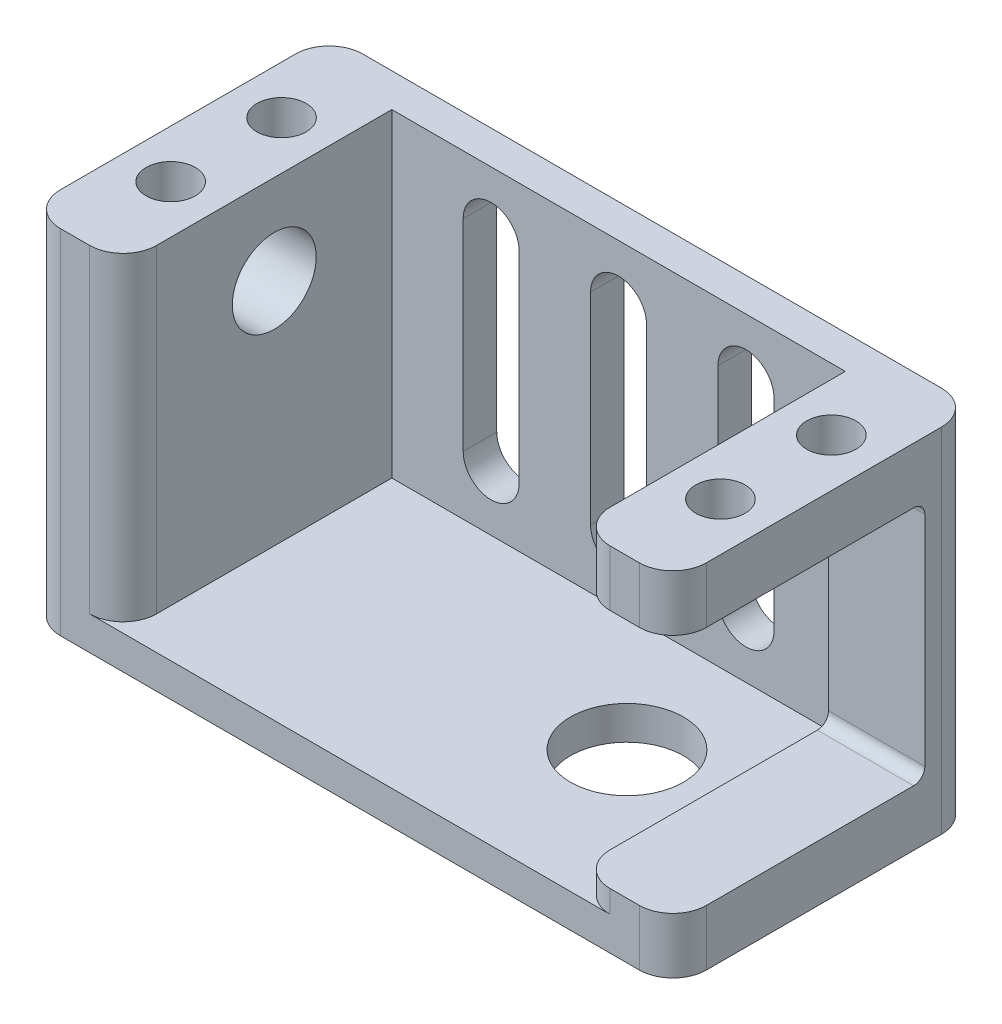
SolidWorks part; units mm, degrees
ref_plane "Front Plane" through (0, 0, 0) normal (0, 0, 1) x (1, 0, 0)
ref_plane "Top Plane" through (0, 0, 0) normal (0, 1, 0) x (1, 0, 0)
ref_plane "Right Plane" through (0, 0, 0) normal (1, 0, 0) x (0, 0, -1)
sketch "Sketch1" plane through (0, 0, 0) normal (0, 1, 0) x (1, 0, 0)
  line L1 (-4.3, -13.5) -> (4.3, -13.5)
  line L2 (-4.3, -13.5) -> (-4.3, 13.5)
  line L3 (-4.3, 13.5) -> (4.3, 13.5)
  line L4 (4.3, -13.5) -> (4.3, 13.5)
  line L5 (-4.3, -13.5) -> (4.3, 13.5) construction
  line L6 (-4.3, 13.5) -> (4.3, -13.5) construction
  point P0 (0, 0)
  dimension "D1" = 8.6
  dimension "D2" = 27
extrude "Boss-Extrude1" add sketch "Sketch1" along normal blind 31.5
sketch "Sketch2" plane through (4.3, 0, 0) normal (1, 0, 0) x (0, 0, -1)
  line L0 (-13.5, 0) -> (13.5, 0)
  line L1 (-13.5, 0) -> (-13.5, 3)
  line L2 (13.5, 0) -> (13.5, 3)
  line L3 (-13.5, 3) -> (13.5, 3)
  line L4 (-13.5, 31.5) -> (-13.5, 0) construction
  line L5 (13.5, 31.5) -> (13.5, 0) construction
  dimension "D1" = 3
extrude "Boss-Extrude2" add sketch "Sketch2" along normal blind 40.5
sketch "Sketch3" plane through (4.3, 0, 0) normal (1, 0, 0) x (0, 0, -1)
  line L0 (10.5, 31.5) -> (10.5, 3)
  line L1 (10.5, 31.5) -> (13.5, 31.5)
  line L2 (10.5, 3) -> (13.5, 3)
  line L3 (13.5, 31.5) -> (13.5, 3)
  line L4 (0, 31.5) -> (0, 3) construction
  line L5 (-13.5, 31.5) -> (13.5, 31.5) construction
  line L6 (13.5, 3) -> (-13.5, 3) construction
  dimension "D1" = 3
extrude "Boss-Extrude3" add sketch "Sketch3" along normal blind 40.5
sketch "Sketch4" plane through (0, 31.5, 0) normal (0, 1, 0) x (1, 0, 0)
  line L0 (44.8, 13.5) -> (44.8, -13.5)
  line L1 (44.8, 13.5) -> (53.4, 13.5)
  line L2 (44.8, -13.5) -> (53.4, -13.5)
  line L3 (53.4, 13.5) -> (53.4, -13.5)
  line L4 (44.8, 13.5) -> (44.8, 10.5) construction
  line L5 (-4.3, -13.5) -> (4.3, -13.5) construction
  dimension "D1" = 8.6
extrude "Boss-Extrude4" add sketch "Sketch4" against normal blind 31.5
sketch "Sketch12" plane through (0, 0, -10.5) normal (0, 0, 1) x (1, 0, 0)
  line L0 (38.43, 8.25) -> (38.43, 26.25)
  line L1 (27.05, 8.25) -> (27.05, 26.25)
  line L2 (22.05, 8.25) -> (22.05, 26.25)
  line L3 (33.43, 8.25) -> (33.43, 26.25)
  line L4 (24.55, 31.5) -> (24.55, 3) construction
  line L5 (4.3, 17.25) -> (44.8, 17.25) construction
  line L7 (44.8, 31.5) -> (4.3, 31.5) construction
  line L8 (44.8, 3) -> (4.3, 3) construction
  line L10 (15.67, 8.25) -> (15.67, 26.25)
  line L13 (4.3, 31.5) -> (4.3, 3) construction
  line L14 (44.8, 31.5) -> (44.8, 3) construction
  line L15 (10.67, 8.25) -> (10.67, 26.25)
  arc A0 (27.05, 26.25) -> (22.05, 26.25) centre (24.55, 26.25) ccw
  arc A1 (27.05, 8.25) -> (22.05, 8.25) centre (24.55, 8.25) cw
  arc A6 (38.43, 26.25) -> (33.43, 26.25) centre (35.93, 26.25) ccw
  arc A7 (38.43, 8.25) -> (33.43, 8.25) centre (35.93, 8.25) cw
  arc A8 (10.67, 8.25) -> (15.67, 8.25) centre (13.17, 8.25) ccw
  arc A9 (10.67, 26.25) -> (15.67, 26.25) centre (13.17, 26.25) cw
  point P2 (24.55, 17.25)
  dimension "D1" = 18
  dimension "D2" = 5
  dimension "D4" = 11.38
  dimension "D3" = 2
extrude "Cut-Extrude6" cut sketch "Sketch12" against normal through all
sketch "Sketch5" plane through (0, 31.5, 0) normal (0, 1, 0) x (1, 0, 0)
  line L0 (-4.3, 0) -> (4.3, 0) construction
  line L1 (4.3, 10.5) -> (4.3, -13.5) construction
  line L3 (4.3, 10.5) -> (4.3, -13.5) construction
  line L6 (-4.3, 13.5) -> (-4.3, -13.5) construction
  line L7 (44.8, 10.5) -> (44.8, -13.5) construction
  circle A0 centre (49.1, 4.95) radius 2.2
  circle A1 centre (49.1, -4.95) radius 2.2
  circle A2 centre (0, 4.95) radius 2.2
  circle A3 centre (0, -4.95) radius 2.2
  dimension "D1" = 4.4
  dimension "D3" = 4.4
  dimension "D6" = 4.3
  dimension "D7" = 4.3
  dimension "D2" = 9.9
  dimension "D4" = 9.9
  dimension "D5" = 4.95
extrude "Cut-Extrude1" cut sketch "Sketch5" against normal blind 5
sketch "Sketch6" plane through (44.8, 0, 0) normal (-1, 0, 0) x (0, 0, 1)
  line L0 (13.5, 26.5) -> (13.5, 5)
  line L1 (13.5, 26.5) -> (-9, 26.5)
  line L2 (13.5, 5) -> (-9, 5)
  line L3 (-9, 26.5) -> (-9, 5)
  line L4 (13.5, 3) -> (13.5, 31.5) construction
  line L5 (1.5, 3) -> (1.5, 31.5) construction
  line L6 (-10.5, 3) -> (13.5, 3) construction
  line L7 (-10.5, 31.5) -> (13.5, 31.5) construction
  line L8 (-10.5, 3) -> (13.5, 3) construction
  line L9 (13.5, 31.5) -> (-13.5, 31.5) construction
  line L10 (-10.5, 31.5) -> (-10.5, 3) construction
  dimension "D1" = 1.5
  dimension "D2" = 5
  dimension "D3" = 2
extrude "Cut-Extrude2" cut sketch "Sketch6" against normal blind 10
sketch "Sketch8" plane through (0, 3, 0) normal (0, 1, 0) x (1, 0, 0)
  line L0 (44.8, 0) -> (4.3, 0) construction
  line L1 (44.8, 10.5) -> (44.8, -13.5) construction
  line L2 (4.3, -13.5) -> (4.3, 10.5) construction
  circle A0 centre (35.8, 0) radius 5.05
  dimension "D2" = 10.1
  dimension "D1" = 9
extrude "Cut-Extrude3" cut sketch "Sketch8" against normal through all
sketch "Sketch9" plane through (-4.3, 0, 0) normal (-1, 0, 0) x (0, 0, 1)
  line L0 (13.5, 31.5) -> (13.5, 0) construction
  circle A0 centre (0, 23.5) radius 1.75
  point P6 (13.5, 15.75)
  dimension "D1" = 3.5
  dimension "D2" = 7.75
extrude "Cut-Extrude4" cut sketch "Sketch9" against normal up to surface (8.6 mm away) up to face at (4.3, 17.25, 1.5)
sketch "Sketch10" plane through (4.3, 0, 0) normal (1, 0, 0) x (0, 0, -1)
  circle A0 centre (0, 23.5) radius 3.75
  circle A1 centre (0, 23.5) radius 1.75 construction
  dimension "D1" = 2
extrude "Cut-Extrude5" cut sketch "Sketch10" against normal offset from surface (6.6 mm away) 2 up to face at (-4.3, 23.5, 1.75)
sketch "Sketch11" plane through (-4.3, 0, 0) normal (-1, 0, 0) x (0, 0, 1)
  line L0 (-13.5, 15.75) -> (13.5, 15.75) construction
  line L1 (-13.5, 31.5) -> (-13.5, 0) construction
  line L2 (-6.9505, 25.25) -> (0, 25.25) construction
  line L3 (-13.5, 21.85) -> (-13.5, 25.15)
  line L4 (-13.5, 25.15) -> (-0.5831, 25.15)
  line L6 (-0.5831, 21.85) -> (-13.5, 21.85)
  line L8 (13.5, 31.5) -> (13.5, 0) construction
  arc A1 (-0.5831, 25.15) -> (-0.5831, 21.85) centre (0, 23.5) ccw
  circle A2 centre (0, 23.5) radius 1.75 construction
  arc A3 (0, 21.75) -> (0, 25.25) centre (0, 23.5) ccw construction
  dimension "D1" = 0.1
extrude "Boss-Extrude5" add sketch "Sketch11" along normal up to surface (2 mm away)
fillet "Fillet1" radius 3 5 edges at (53.4, 29, 13.5) (53.4, 15.75, -13.5) (4.3, 17.25, 13.5) (44.8, 29, 13.5) (44.8, 4, 13.5)
fillet "Fillet2" radius 3 3 edges at (-4.3, 10.925, -13.5) (-4.3, 28.325, -13.5) (-4.3, 15.75, 13.5)
fillet "Fillet3" radius 1 2 edges at (49.1, 26.5, -9) (49.1, 5, -9)
fillet "Fillet4" radius 0.25 2 edges at (-5.3, 21.85, -0.5831) (-5.3, 25.15, -0.5831)
fillet "Fillet5" radius 1.5 1 edges at (-6.3, 23.5, -13.5)
